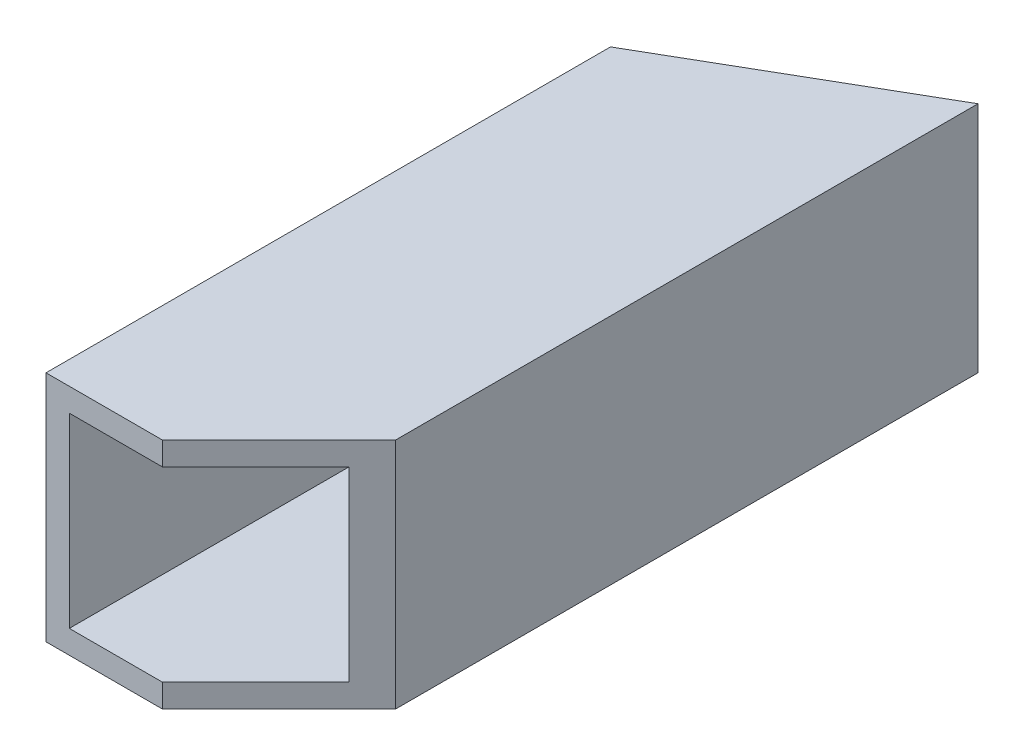
SolidWorks part; units mm, degrees
ref_plane "Front Plane" through (0, 0, 0) normal (0, 0, 1) x (1, 0, 0)
ref_plane "Top Plane" through (0, 0, 0) normal (0, 1, 0) x (1, 0, 0)
ref_plane "Right Plane" through (0, 0, 0) normal (1, 0, 0) x (0, 0, -1)
sketch "Sketch2" plane through (0, 0, 0) normal (0, 0, -1) x (1, 0, 0)
  line L0 (-20, -20) -> (-20, 20)
  line L1 (-25, -25) -> (25, -25)
  line L2 (-25, -25) -> (-25, 25)
  line L3 (-25, 25) -> (25, 25)
  line L4 (25, -25) -> (25, 25)
  line L5 (-20, 20) -> (20, 20)
  line L6 (20, -20) -> (20, 20)
  line L7 (-20, -20) -> (20, -20)
  dimension "tube_width" = 50
  dimension "tube_height" = 50
  dimension "D1" = 25
  dimension "D3" = 25
  dimension "D2" = 5
extrude "Boss-Extrude1" add sketch "Sketch2" against normal blind 150
sketch "Sketch3" plane through (0, -25, 0) normal (0, -1, 0) x (1, 0, 0)
  line L0 (0, 150) -> (25, 125)
  line L1 (25, 150) -> (-25, 150) construction
  line L2 (25, 150) -> (25, 0) construction
  line L3 (25, 125) -> (25, 150)
  line L4 (25, 150) -> (0, 150)
  dimension "D1" = 45
extrude "Cut-Extrude1" cut sketch "Sketch3" against normal through all
sketch "Sketch4" plane through (0, -25, 0) normal (0, -1, 0) x (1, 0, 0)
  line L0 (25, 0) -> (-25, 28.8675)
  line L1 (-25, 150) -> (-25, 0) construction
  line L2 (-25, 28.8675) -> (-25, 0)
  line L3 (-25, 0) -> (25, 0)
  dimension "D1" = 30
extrude "Cut-Extrude2" cut sketch "Sketch4" against normal through all
equation "\"D1@Sketch2\"=\"tube_width@Sketch2\"/2"
equation "\"D3@Sketch2\"=\"tube_height@Sketch2\"/2"
